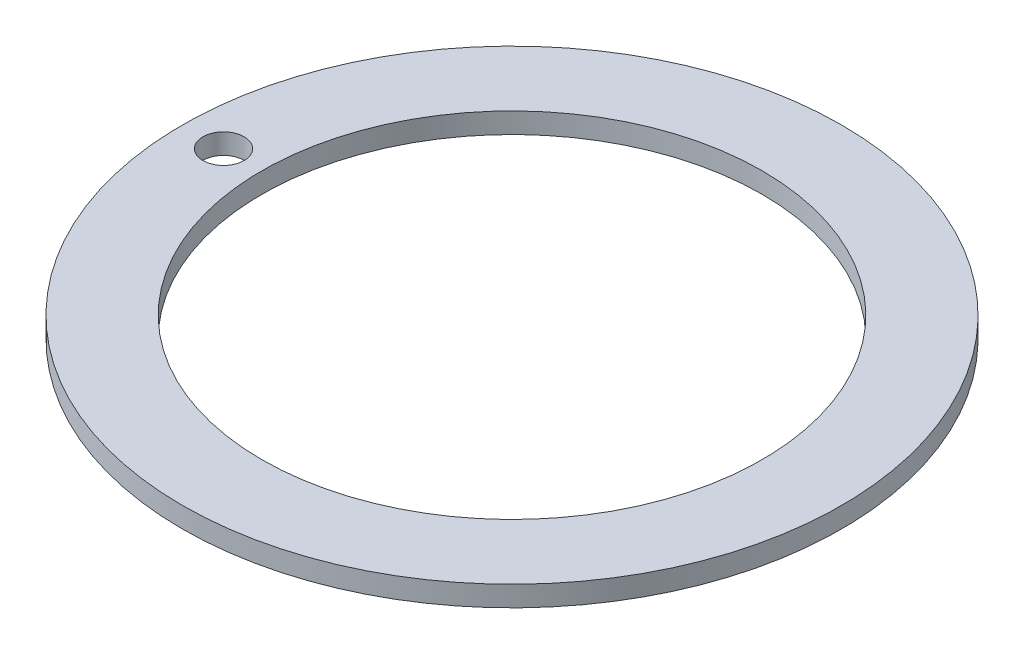
SolidWorks part; units mm, degrees
ref_plane "Front Plane" through (0, 0, 0) normal (0, 0, 1) x (1, 0, 0)
ref_plane "Top Plane" through (0, 0, 0) normal (0, 1, 0) x (1, 0, 0)
ref_plane "Right Plane" through (0, 0, 0) normal (1, 0, 0) x (0, 0, -1)
sketch "Sketch1" plane through (0, 0, 0) normal (0, 1, 0) x (1, 0, 0)
  circle A0 centre (0, 0) radius 38.0746
  circle A1 centre (0, 0) radius 28.9052
  dimension "D1" = 57.8104
  dimension "D2" = 76.1492
extrude "Boss-Extrude1" add sketch "Sketch1" along normal blind 2.3622
sketch "Sketch2" plane through (0, 2.3622, 0) normal (0, 1, 0) x (1, 0, 0)
  circle A0 centre (-33.3299, 0) radius 2.3812
extrude "Cut-Extrude2" cut sketch "Sketch2" against normal blind 2.54
